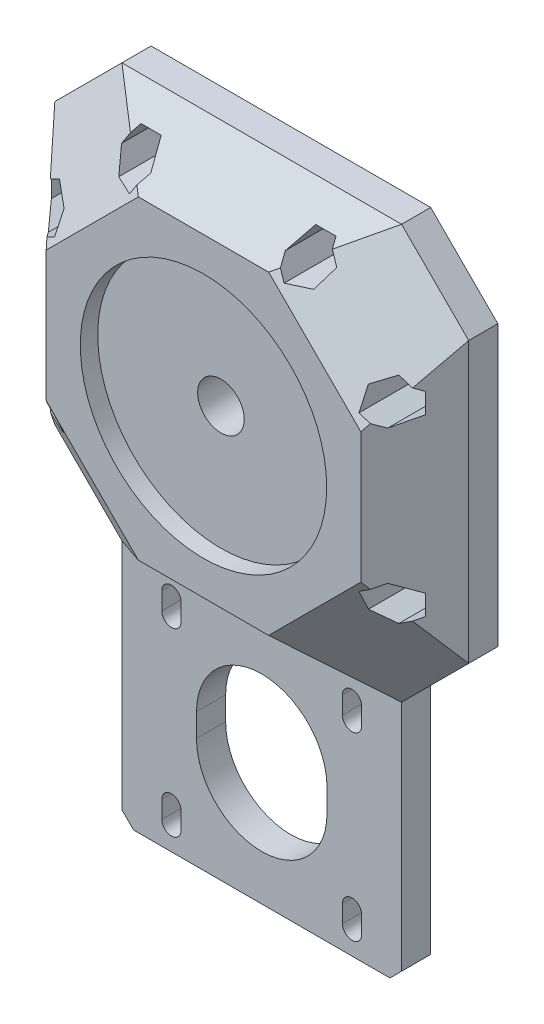
SolidWorks part; units mm, degrees
ref_plane "前视基准面" through (0, 0, 0) normal (0, 0, 1) x (1, 0, 0)
ref_plane "上视基准面" through (0, 0, 0) normal (0, 1, 0) x (1, 0, 0)
ref_plane "右视基准面" through (0, 0, 0) normal (1, 0, 0) x (0, 0, -1)
other "Configuration Table"
sketch "草图1" plane through (0, 0, 0) normal (0, 0, 1) x (1, 0, 0)
  line L16 (0, 67.7639) -> (0, -15.4198) construction
  line L17 (-51.844, 0) -> (59.8456, 0) construction
  line L18 (24, 35.52) -> (35.52, 24)
  line L20 (-35.52, -24) -> (-35.52, 24)
  line L21 (-24, 35.52) -> (24, 35.52)
  line L22 (35.52, -24) -> (35.52, 24)
  line L23 (-29.76, -29.76) -> (29.76, 29.76) construction
  line L24 (-29.76, 29.76) -> (29.76, -29.76) construction
  line L25 (-24, 35.52) -> (-35.52, 24)
  line L26 (24, -35.52) -> (35.52, -24)
  line L27 (-24, -35.52) -> (-35.52, -24)
  line L28 (-24, -35.52) -> (-24, -77.52)
  line L29 (-24, -77.52) -> (24, -77.52)
  line L30 (24, -77.52) -> (24, -35.52)
  line L31 (24, -56.52) -> (-24, -56.52) construction
  line L32 (0, -54.52) -> (0, -58.52) construction
  line L33 (11.2, -54.52) -> (11.2, -58.52)
  line L34 (-11.2, -54.52) -> (-11.2, -58.52)
  line L35 (-15.5, -42.52) -> (-15.5, -39.52) construction
  line L36 (-15.5, -72.02) -> (15.5, -72.02) construction
  line L37 (-15.5, -72.02) -> (-15.5, -41.02) construction
  line L38 (-15.5, -41.02) -> (15.5, -41.02) construction
  line L39 (15.5, -72.02) -> (15.5, -41.02) construction
  line L40 (-15.5, -72.02) -> (15.5, -41.02) construction
  line L41 (-15.5, -41.02) -> (15.5, -72.02) construction
  line L42 (-17.15, -42.52) -> (-17.15, -39.52)
  line L43 (-13.85, -42.52) -> (-13.85, -39.52)
  line L44 (15.5, -42.52) -> (15.5, -39.52) construction
  line L45 (17.15, -42.52) -> (17.15, -39.52)
  line L46 (13.85, -42.52) -> (13.85, -39.52)
  line L47 (15.5, -70.52) -> (15.5, -73.52) construction
  line L48 (17.15, -70.52) -> (17.15, -73.52)
  line L49 (13.85, -70.52) -> (13.85, -73.52)
  line L50 (-15.5, -70.52) -> (-15.5, -73.52) construction
  line L51 (-17.15, -70.52) -> (-17.15, -73.52)
  line L52 (-13.85, -70.52) -> (-13.85, -73.52)
  arc A1 (11.2, -54.52) -> (-11.2, -54.52) centre (0, -54.52) ccw
  arc A2 (-11.2, -58.52) -> (11.2, -58.52) centre (0, -58.52) ccw
  arc A7 (-17.15, -42.52) -> (-13.85, -42.52) centre (-15.5, -42.52) ccw
  arc A8 (-13.85, -39.52) -> (-17.15, -39.52) centre (-15.5, -39.52) ccw
  arc A9 (17.15, -42.52) -> (13.85, -42.52) centre (15.5, -42.52) cw
  arc A10 (13.85, -39.52) -> (17.15, -39.52) centre (15.5, -39.52) cw
  arc A11 (17.15, -70.52) -> (13.85, -70.52) centre (15.5, -70.52) ccw
  arc A12 (13.85, -73.52) -> (17.15, -73.52) centre (15.5, -73.52) ccw
  arc A13 (-17.15, -70.52) -> (-13.85, -70.52) centre (-15.5, -70.52) cw
  arc A14 (-13.85, -73.52) -> (-17.15, -73.52) centre (-15.5, -73.52) cw
  point P0 (0, 0)
  point P23 (0, -56.52)
  point P30 (0, -56.52)
  point P36 (-15.5, -41.02)
  point P44 (15.5, -41.02)
  point P51 (15.5, -72.02)
  point P58 (-15.5, -72.02)
  dimension "D4" = 4
  dimension "D9" = 3
  dimension "D1" = 135
  dimension "D2" = 48
  dimension "D3" = 42
  dimension "D5" = 48
  dimension "D6" = 0
  dimension "D7" = 31
  dimension "D8" = 31
extrude "凸台-拉伸1" add sketch "草图1" along normal blind 5
ref_plane "基准面1" through (0, 0, 15) normal (0, 0, 1) x (1, 0, 0)
sketch "草图3" plane through (0, 0, 15) normal (0, 0, 1) x (1, 0, 0)
  line L1 (11.1838, 27) -> (-11.1838, 27)
  line L2 (-11.1838, 27) -> (-27, 11.1838)
  line L3 (-27, 11.1838) -> (-27, -11.1838)
  line L4 (-27, -11.1838) -> (-11.1838, -27)
  line L5 (-11.1838, -27) -> (11.1838, -27)
  line L6 (11.1838, -27) -> (27, -11.1838)
  line L7 (27, -11.1838) -> (27, 11.1838)
  line L8 (27, 11.1838) -> (11.1838, 27)
  circle A2 centre (0, 0) radius 27 construction
  dimension "D1" = 54
sketch "草图4" plane through (0, 0, 5) normal (0, 0, 1) x (1, 0, 0)
  line L0 (-24, -35.52) -> (24, -35.52)
  line L10 (24, -77.52) -> (24, -35.52)
  line L11 (24, -35.52) -> (35.52, -24)
  line L12 (35.52, -24) -> (35.52, 24)
  line L13 (35.52, 24) -> (24, 35.52)
  line L14 (24, 35.52) -> (-24, 35.52)
  line L15 (-24, 35.52) -> (-35.52, 24)
  line L16 (-35.52, 24) -> (-35.52, -24)
  line L17 (-35.52, -24) -> (-24, -35.52)
  line L18 (-24, -35.52) -> (-24, -77.52)
  line L19 (-24, -77.52) -> (24, -77.52)
  line L21 (24, -35.52) -> (35.52, -24)
  line L22 (35.52, -24) -> (35.52, 24)
  line L23 (35.52, 24) -> (24, 35.52)
  line L24 (24, 35.52) -> (-24, 35.52)
  line L25 (-24, 35.52) -> (-35.52, 24)
  line L26 (-35.52, 24) -> (-35.52, -24)
  line L27 (-35.52, -24) -> (-24, -35.52)
  dimension "D1" = 0
loft "放样1" add profiles "草图3", "草图4"
sketch "草图5" plane through (0, 0, 15) normal (0, 0, 1) x (1, 0, 0)
  circle A0 centre (0, 0) radius 21.15
  dimension "D1" = 42.3
extrude "切除-拉伸1" cut sketch "草图5" against normal blind 3
sketch "草图6" plane through (0, 0, 12) normal (0, 0, 1) x (1, 0, 0)
  circle A0 centre (0, 0) radius 4
  dimension "D1" = 8
extrude "切除-拉伸2" cut sketch "草图6" against normal blind 37
sketch "草图7" plane through (0, 0, 0) normal (0, 0, -1) x (-1, 0, 0)
  line L0 (35.52, 24) -> (35.52, -24) construction
  line L1 (29.12, 23.4643) -> (29.12, -24.5357) construction
  line L2 (-17.5829, 0) -> (13.1378, 0) construction
  circle A0 centre (29.12, 15) radius 1.8
  circle A1 centre (29.12, -15) radius 1.8
  circle A4 centre (-29.12, -15) radius 1.8
  circle A5 centre (-29.12, 15) radius 1.8
  circle A6 centre (-15, 29.12) radius 1.8
  circle A7 centre (15, 29.12) radius 1.8
  circle A8 centre (15, -29.12) radius 1.8 [skipped]
  circle A9 centre (-15, -29.12) radius 1.8 [skipped]
  point P26 (0, 0)
  dimension "D2" = 3.6
  dimension "D4" = 30
  dimension "D1" = 6.4
  dimension "D3" = 4
extrude "切除-拉伸3" cut sketch "草图7" against normal blind 37
sketch "草图8" plane through (0, 0, 15) normal (0, 0, 1) x (1, 0, 0)
  line L0 (-42.8131, 0) -> (-8.3645, 0) construction
  line L1 (-29.12, -11.5359) -> (-32.12, -13.2679)
  line L2 (-32.12, -13.2679) -> (-32.12, -16.7321)
  line L3 (-32.12, -16.7321) -> (-29.12, -18.4641)
  line L4 (-29.12, -18.4641) -> (-26.12, -16.7321)
  line L5 (-26.12, -16.7321) -> (-26.12, -13.2679)
  line L6 (-26.12, -13.2679) -> (-29.12, -11.5359)
  line L7 (-26.12, 13.2679) -> (-29.12, 11.5359)
  line L8 (-26.12, 16.7321) -> (-26.12, 13.2679)
  line L9 (-29.12, 18.4641) -> (-26.12, 16.7321)
  line L10 (-32.12, 16.7321) -> (-29.12, 18.4641)
  line L11 (-32.12, 13.2679) -> (-32.12, 16.7321)
  line L12 (-29.12, 11.5359) -> (-32.12, 13.2679)
  line L49 (13.2679, 26.12) -> (11.5359, 29.12)
  line L50 (11.5359, 29.12) -> (13.2679, 32.12)
  line L51 (13.2679, 32.12) -> (16.7321, 32.12)
  line L52 (16.7321, 32.12) -> (18.4641, 29.12)
  line L53 (18.4641, 29.12) -> (16.7321, 26.12)
  line L54 (16.7321, 26.12) -> (13.2679, 26.12)
  line L55 (-11.5359, 29.12) -> (-13.2679, 32.12)
  line L56 (-13.2679, 32.12) -> (-16.7321, 32.12)
  line L57 (-16.7321, 32.12) -> (-18.4641, 29.12)
  line L58 (-18.4641, 29.12) -> (-16.7321, 26.12)
  line L59 (-16.7321, 26.12) -> (-13.2679, 26.12)
  line L60 (-13.2679, 26.12) -> (-11.5359, 29.12)
  line L61 (26.12, -13.2679) -> (29.12, -11.5359)
  line L62 (29.12, -11.5359) -> (32.12, -13.2679)
  line L63 (32.12, -13.2679) -> (32.12, -16.7321)
  line L64 (32.12, -16.7321) -> (29.12, -18.4641)
  line L65 (29.12, -18.4641) -> (26.12, -16.7321)
  line L66 (26.12, -16.7321) -> (26.12, -13.2679)
  line L67 (29.12, 11.5359) -> (32.12, 13.2679)
  line L68 (32.12, 13.2679) -> (32.12, 16.7321)
  line L69 (32.12, 16.7321) -> (29.12, 18.4641)
  line L70 (29.12, 18.4641) -> (26.12, 16.7321)
  line L71 (26.12, 16.7321) -> (26.12, 13.2679)
  line L72 (26.12, 13.2679) -> (29.12, 11.5359)
  line L85 (11.5359, -29.12) -> (13.2679, -32.12) [skipped]
  line L86 (13.2679, -32.12) -> (16.7321, -32.12) [skipped]
  line L87 (16.7321, -32.12) -> (18.4641, -29.12) [skipped]
  line L88 (18.4641, -29.12) -> (16.7321, -26.12) [skipped]
  line L89 (16.7321, -26.12) -> (13.2679, -26.12) [skipped]
  line L90 (13.2679, -26.12) -> (11.5359, -29.12) [skipped]
  line L91 (-13.2679, -26.12) -> (-11.5359, -29.12) [skipped]
  line L92 (-11.5359, -29.12) -> (-13.2679, -32.12) [skipped]
  line L93 (-13.2679, -32.12) -> (-16.7321, -32.12) [skipped]
  line L94 (-16.7321, -32.12) -> (-18.4641, -29.12) [skipped]
  line L95 (-18.4641, -29.12) -> (-16.7321, -26.12) [skipped]
  line L96 (-16.7321, -26.12) -> (-13.2679, -26.12) [skipped]
  circle A0 centre (-29.12, -15) radius 3 construction
  point P57 (1.4, 1.4)
  point P58 (0, 0)
  dimension "D1" = 6
  dimension "D2" = 4
extrude "切除-拉伸4" cut sketch "草图8" against normal blind 12
chamfer "倒角1" distance 2 angle 45 2 edges at (24, -77.52, 2.5) (-24, -77.52, 2.5)
